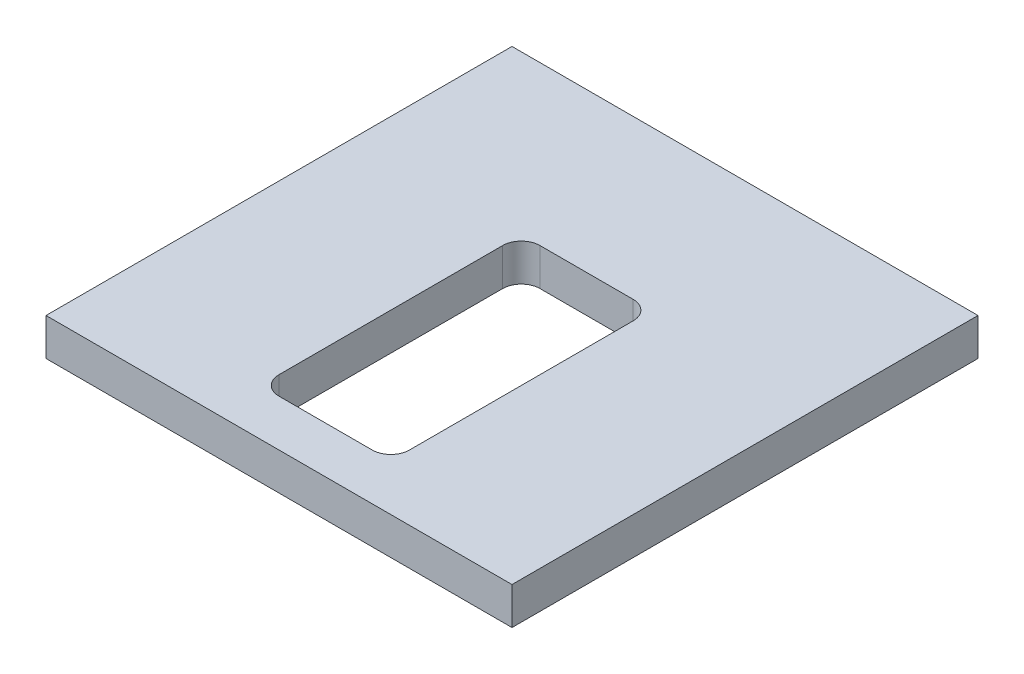
SolidWorks part; units mm, degrees
material "2024 Alloy"
ref_plane "Front Plane" through (0, 0, 0) normal (0, 0, 1) x (1, 0, 0)
ref_plane "Top Plane" through (0, 0, 0) normal (0, 1, 0) x (1, 0, 0)
ref_plane "Right Plane" through (0, 0, 0) normal (1, 0, 0) x (0, 0, -1)
sketch "Sketch1" plane through (0, 0, 0) normal (0, 1, 0) x (1, 0, 0)
  line L1 (-12.5, -12.5) -> (12.5, -12.5)
  line L2 (-12.5, -12.5) -> (-12.5, 12.5)
  line L3 (-12.5, 12.5) -> (12.5, 12.5)
  line L4 (12.5, -12.5) -> (12.5, 12.5)
  line L5 (-12.5, -12.5) -> (12.5, 12.5) construction
  line L6 (-12.5, 12.5) -> (12.5, -12.5) construction
  point P0 (0, 0)
  dimension "D1" = 25
extrude "Boss-Extrude1" add sketch "Sketch1" along normal mid plane 2
sketch "Sketch2" plane through (0, 1, 0) normal (0, 1, 0) x (1, 0, 0)
  line L0 (-12.5, -12.5) -> (12.5, -12.5) construction
  line L1 (-3.5, 4) -> (3.5, 4)
  line L2 (-3.5, 4) -> (-3.5, -10)
  line L3 (-3.5, -10) -> (3.5, -10)
  line L4 (3.5, 4) -> (3.5, -10)
  point P6 (0, -10)
  dimension "D1" = 7
  dimension "D2" = 14
  dimension "D3" = 2.5
extrude "Cut-Extrude1" cut sketch "Sketch2" against normal up to next
fillet "Fillet1" radius 1 4 edges at (3.5, 0, 10) (-3.5, 0, 10) (3.5, 0, -4) (-3.5, 0, -4)
